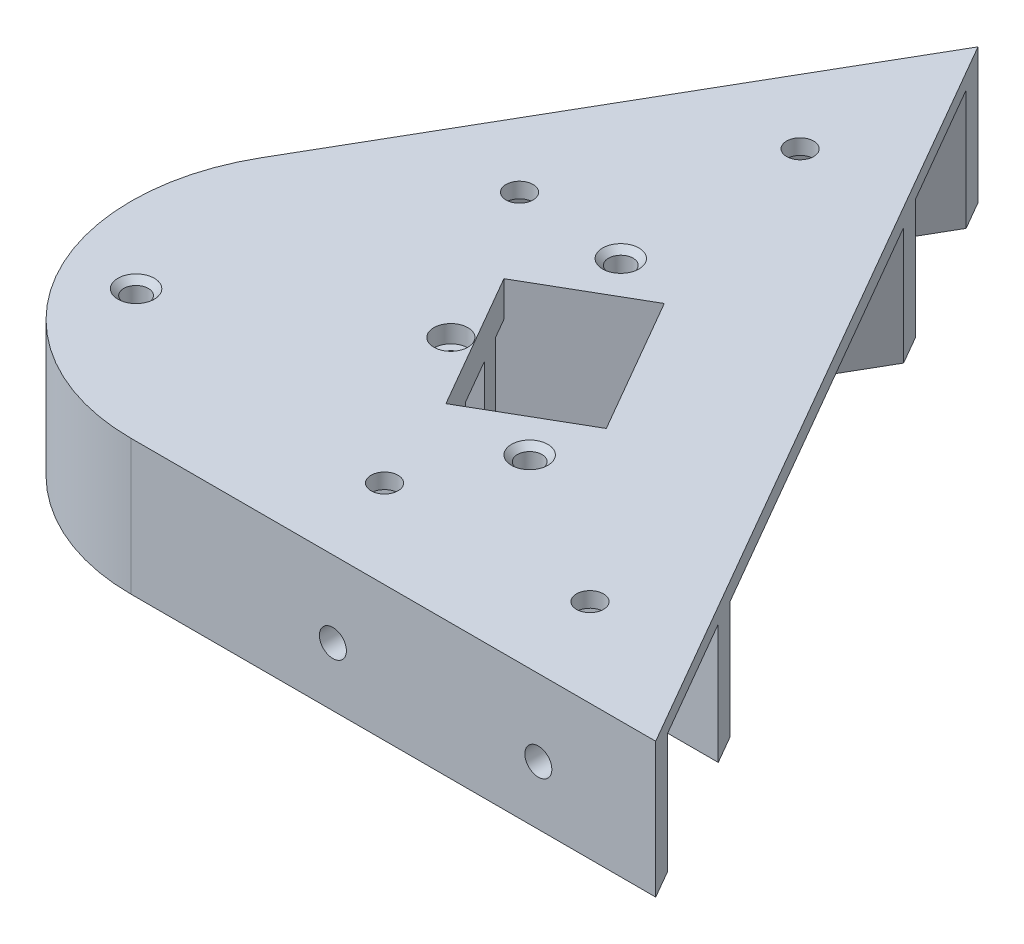
SolidWorks part; units mm, degrees
other "Markup1"
sketch "Sketch26" plane through (25.6218, 0, -129.9038) normal (-0.1134, -0.9932, -0.0259) x (0.9576, -0.1162, 0.2636)
ref_plane "Front Plane" through (0, 0, 0) normal (0, 0, 1) x (1, 0, 0)
ref_plane "Top Plane" through (0, 0, 0) normal (0, 1, 0) x (1, 0, 0)
ref_plane "Right Plane" through (0, 0, 0) normal (1, 0, 0) x (0, 0, -1)
sketch "Sketch1" plane through (0, 0, 0) normal (0, 1, 0) x (1, 0, 0)
  line L0 (0, 0) -> (150, 0)
  line L1 (0, 0) -> (75, 129.9038)
  line L2 (75, 129.9038) -> (150, 0)
  dimension "D1" = 60
  dimension "D2" = 150
  dimension "D3" = 60
extrude "Boss-Extrude1" add sketch "Sketch1" along normal blind 23
sketch "Sketch2" plane through (0, 0, 0) normal (0, 1, 0) x (1, 0, 0)
  line L0 (0, 0) -> (150, 0) construction
  line L1 (74, 5) -> (174, 5) construction
  line L2 (74, 5) -> (74, 25) construction
  line L3 (74, 25) -> (174, 25) construction
  line L4 (174, 5) -> (174, 25) construction
  line L5 (41.3301, 61.5859) -> (91.3301, 148.1884) construction
  line L6 (91.3301, 148.1884) -> (108.6506, 138.1884) construction
  line L7 (108.6506, 138.1884) -> (58.6506, 51.5859) construction
  line L8 (58.6506, 51.5859) -> (41.3301, 61.5859) construction
  line L9 (75, 129.9038) -> (0, 0) construction
  line L10 (108.9238, 138.2616) -> (58.7238, 51.3127)
  line L11 (58.7238, 51.3127) -> (41.0569, 61.5127)
  line L12 (41.0569, 61.5127) -> (91.2569, 148.4616)
  line L13 (91.2569, 148.4616) -> (108.9238, 138.2616)
  line L14 (73.8, 25.2) -> (174.2, 25.2)
  line L15 (174.2, 4.8) -> (174.2, 25.2)
  line L16 (73.8, 4.8) -> (174.2, 4.8)
  line L17 (73.8, 4.8) -> (73.8, 25.2)
  dimension "D1" = 20
  dimension "D2" = 5
  dimension "D3" = 74
  dimension "D4" = 20
  dimension "D5" = 74
  dimension "D6" = 5
  dimension "D7" = 100
  dimension "D8" = 100
  dimension "D9" = 0.2
  dimension "D10" = 0.2
extrude "Cut-Extrude2" cut sketch "Sketch2" along normal blind 20.4
sketch "Sketch4" plane through (0, 0, 0) normal (0, 1, 0) x (1, 0, 0)
  line L4 (135.4508, 25.2) -> (89.5492, 104.7038) construction
  line L6 (0, 0) -> (52.9457, 91.7047) construction
  line L7 (68.4424, 27.9682) -> (51.1219, 17.9682) construction
  line L8 (68.4424, 27.9682) -> (58.4424, 45.2887) construction
  line L9 (58.4424, 45.2887) -> (41.1219, 35.2887) construction
  line L10 (51.1219, 17.9682) -> (41.1219, 35.2887) construction
  line L11 (68.4424, 27.9682) -> (41.1219, 35.2887) construction
  line L12 (58.4424, 45.2887) -> (51.1219, 17.9682) construction
  line L13 (58.5156, 45.5619) -> (40.8487, 35.3619)
  line L14 (75, 129.9038) -> (0, 0) construction
  line L15 (0, 0) -> (130.8784, 0) construction
  line L16 (0, 0) -> (150, 0) construction
  line L17 (51.0487, 17.695) -> (40.8487, 35.3619)
  line L18 (68.7156, 27.895) -> (51.0487, 17.695)
  line L19 (68.7156, 27.895) -> (58.5156, 45.5619)
  point P0 (54.7821, 31.6285)
  dimension "D1" = 20
  dimension "D2" = 20
  dimension "D4" = 0.2
extrude "Cut-Extrude3" cut sketch "Sketch4" along normal blind 20
sketch "Sketch7" plane through (0, 0, 0) normal (-0.866, 0, -0.5) x (-0.5, 0, 0.866)
  line L0 (-150, 0) -> (0, 0) construction
  line L1 (-150, 23) -> (-150, 0) construction
  circle A0 centre (-130, 10) radius 2.3
  circle A1 centre (-95, 10) radius 2.3
  dimension "D1" = 4.6
  dimension "D2" = 10
  dimension "D3" = 20
  dimension "D4" = 35
extrude "Cut-Extrude6" cut sketch "Sketch7" against normal blind 10
sketch "Sketch8" plane through (0, 0, 0) normal (0, 0, 1) x (1, 0, 0)
  line L0 (150, 23) -> (150, 0) construction
  line L1 (0, 0) -> (150, 0) construction
  circle A0 centre (130, 10) radius 2.3
  circle A1 centre (95, 10) radius 2.3
  dimension "D1" = 4.6
  dimension "D2" = 20
  dimension "D3" = 10
  dimension "D4" = 35
extrude "Cut-Extrude7" cut sketch "Sketch8" against normal blind 10
ref_plane "Plane1" through (42.4846, 0, -24.5285) normal (0.866, 0, -0.5) x (-0.5, 0, -0.866)
fillet "Fillet3" radius 35 1 edges at (0, 11.5, 0)
sketch "Sketch22" plane through (0, 0, 0) normal (0, -1, 0) x (1, 0, 0)
  line L0 (76.2572, -28.4387) -> (62.7572, -51.8213)
  line L1 (62.7572, -51.8213) -> (86.1399, -65.3213)
  line L2 (86.1399, -65.3213) -> (99.6399, -41.9387)
  line L3 (99.6399, -41.9387) -> (76.2572, -28.4387)
  line L5 (135.4508, -25.2) -> (89.5492, -104.7038) construction
  dimension "D1" = 80.26
  dimension "D2" = 13.5
  dimension "D3" = 13.5
  dimension "D4" = 27
extrude "Cut-Extrude11" cut sketch "Sketch22" against normal through all both and the other way through all
sketch "Sketch21" plane through (0, 0, 0) normal (0, -1, 0) x (1, 0, 0)
  line L0 (132.6795, -30) -> (109.9968, -30)
  line L1 (109.9968, -30) -> (80.9791, -80.26)
  line L2 (80.9791, -80.26) -> (92.3205, -99.9038)
  line L3 (92.3205, -99.9038) -> (132.6795, -30)
  line L4 (135.4508, -25.2) -> (89.5492, -104.7038) construction
  line L5 (135.4508, -25.2) -> (73.8, -25.2) construction
  line L7 (58.7238, -51.3127) -> (89.5492, -104.7038) construction
  line L8 (58.7238, -51.3127) -> (89.5492, -104.7038) construction
  line L9 (86.1399, -65.3213) -> (99.6399, -41.9387) construction
  dimension "D1" = 3
  dimension "D2" = 4.8
  dimension "D3" = 4.8
extrude "Cut-Extrude10" cut sketch "Sketch21" against normal offset from surface (20 mm away) 3 up to face at (81.1985, 23, -46.88)
sketch "Sketch27" plane through (0, 23, 0) normal (0, 1, 0) x (1, 0, 0)
  line L0 (76.2572, 28.4387) -> (62.7572, 51.8213)
  line L1 (62.7572, 51.8213) -> (68.8194, 55.3213)
  line L2 (62.7572, 51.8213) -> (86.1399, 65.3213) construction
  line L3 (68.8194, 55.3213) -> (82.3194, 31.9387)
  line L4 (99.6399, 41.9387) -> (76.2572, 28.4387) construction
  line L5 (82.3194, 31.9387) -> (76.2572, 28.4387)
  dimension "D1" = 7
extrude "Boss-Extrude3" add sketch "Sketch27" against normal blind 6
sketch "Sketch28" plane through (0, 17, 0) normal (0, -1, 0) x (1, 0, 0)
  line L0 (74.2572, -31.9028) -> (64.7572, -48.3572)
  line L3 (64.7572, -48.3572) -> (70.8194, -51.8572)
  line L4 (70.8194, -51.8572) -> (80.3194, -35.4028)
  line L5 (80.3194, -35.4028) -> (74.2572, -31.9028)
  line L6 (76.2572, -28.4387) -> (82.3194, -31.9387) construction
  line L7 (62.7572, -51.8213) -> (86.1399, -65.3213) construction
  line L8 (82.3194, -31.9387) -> (68.8194, -55.3213) construction
  line L9 (76.2572, -28.4387) -> (62.7572, -51.8213) construction
  dimension "D2" = 4
  dimension "D3" = 4
extrude "Boss-Extrude4" add sketch "Sketch28" along normal up to surface (17 mm away) up to face at (88.3834, 0, -51.0282)
sketch "Sketch29" plane through (0, 0, 0) normal (0, -1, 0) x (1, 0, 0)
  line L0 (77.8194, -39.7329) -> (71.7572, -36.2329)
  line L1 (70.8194, -51.8572) -> (80.3194, -35.4028) construction
  line L2 (71.7572, -36.2329) -> (67.2572, -44.0271)
  line L3 (67.2572, -44.0271) -> (73.3194, -47.5271)
  line L4 (73.3194, -47.5271) -> (77.8194, -39.7329)
  line L5 (80.3194, -35.4028) -> (74.2572, -31.9028) construction
  line L6 (64.7572, -48.3572) -> (70.8194, -51.8572) construction
  line L7 (76.2572, -28.4387) -> (74.2572, -31.9028) construction
  dimension "D1" = 5
  dimension "D2" = 5
extrude "Cut-Extrude14" cut sketch "Sketch29" against normal up to surface (17 mm away) up to face at (78.2883, 17, -31.9207)
sketch "Sketch30" plane through (0, 17, 0) normal (0, -1, 0) x (1, 0, 0)
  line L0 (75.5694, -43.63) -> (63.6156, -36.7285) construction
  line L1 (77.8194, -39.7329) -> (73.3194, -47.5271) construction
  line L2 (68.7156, -27.895) -> (58.5156, -45.5619) construction
  circle A0 centre (72.9713, -42.13) radius 1.5
  dimension "D1" = 3
  dimension "D2" = 3
extrude "Cut-Extrude15" cut sketch "Sketch30" against normal through all
sketch "Sketch31" plane through (0, 23, 0) normal (0, 1, 0) x (1, 0, 0)
  circle A0 centre (72.9713, 42.13) radius 2.9
  dimension "D1" = 5.8
extrude "Cut-Extrude17" cut sketch "Sketch31" against normal blind 3
sketch "Sketch32" plane through (0, 0, -30) normal (0, 0, -1) x (-1, 0, 0)
  line L0 (-132.6795, 10) -> (-109.9968, 10) construction
  line L1 (-132.6795, 20) -> (-132.6795, 0) construction
  line L2 (-109.9968, 20) -> (-109.9968, 0) construction
  circle A0 centre (-121.3381, 10) radius 2.3
  dimension "D1" = 4.6
extrude "Cut-Extrude18" cut sketch "Sketch32" against normal blind 10
sketch "Sketch33" plane through (25.9808, 0, 15) normal (0.866, 0, 0.5) x (0.5, 0, -0.866)
  line L0 (109.9968, 10) -> (132.6795, 10) construction
  line L1 (109.9968, 20) -> (109.9968, 0) construction
  line L2 (132.6795, 20) -> (132.6795, 0) construction
  circle A0 centre (121.3381, 10) radius 2.3
  dimension "D1" = 4.6
extrude "Cut-Extrude19" cut sketch "Sketch33" against normal blind 10
sketch "Sketch34" plane through (45.9487, 0, -26.5285) normal (0.866, 0, -0.5) x (-0.5, 0, -0.866)
  line L0 (-10.2, 10) -> (10.2, 10) construction
  line L1 (-10.2, 20) -> (-10.2, 0) construction
  line L2 (10.2, 20) -> (10.2, 0) construction
  circle A0 centre (0, 10) radius 2.3
  dimension "D1" = 4.6
extrude "Cut-Extrude20" cut sketch "Sketch34" against normal through all
ref_plane "Plane2" through (41.6185, 0, -24.0285) normal (0.866, 0, -0.5) x (-0.5, 0, -0.866)
sketch "Sketch35" plane through (41.6185, 0, -24.0285) normal (0.866, 0, -0.5) x (-0.5, 0, -0.866)
  circle A0 centre (0, 10) radius 4
  dimension "D1" = 8
extrude "Cut-Extrude21" cut sketch "Sketch35" against normal through all
sketch "Sketch36" plane through (0, 23, 0) normal (0, 1, 0) x (1, 0, 0)
  line L0 (0, 0) -> (112.5, 64.9519) construction
  line L1 (150, 0) -> (75, 129.9038) construction
  circle A0 centre (38.9711, 22.5) radius 2.1
  dimension "D1" = 4.2
  dimension "D2" = 45
extrude "Cut-Extrude22" cut sketch "Sketch36" against normal blind 5
sketch "Sketch37" plane through (0, 23, 0) normal (0, 1, 0) x (1, 0, 0)
  line L0 (0, 0) -> (98.694, 88.8645) construction
  line L1 (150, 0) -> (75, 129.9038) construction
  line L3 (0, 0) -> (112.5, 64.9519) construction
  line L4 (0, 0) -> (126.306, 41.0393) construction
  circle A0 centre (97.0078, 31.5197) radius 2.1
  circle A1 centre (75.8008, 68.2513) radius 2.1
  dimension "D5" = 4.2
  dimension "D6" = 4.2
  dimension "D1" = 12
  dimension "D2" = 12
  dimension "D3" = 102
  dimension "D4" = 102
extrude "Cut-Extrude23" cut sketch "Sketch37" against normal blind 5
sketch "Sketch38" plane through (0, 20.4, 0) normal (0, -1, 0) x (1, 0, 0)
  line L0 (49.8904, -56.4127) -> (83.6603, -114.9038) construction
  line L1 (41.0569, -61.5127) -> (58.7238, -51.3127) construction
  line L2 (77.7713, -125.1038) -> (89.5492, -104.7038) construction
  line L3 (73.8, -15) -> (141.3397, -15) construction
  line L4 (73.8, -25.2) -> (73.8, -4.8) construction
  line L5 (135.4508, -25.2) -> (147.2287, -4.8) construction
  line L6 (41.0569, -61.5127) -> (58.7238, -51.3127) construction
  circle A0 centre (88.8, -15) radius 2.3
  circle A1 centre (123.8, -15) radius 2.3
  circle A2 centre (57.3904, -69.4031) radius 2.3
  circle A3 centre (74.8904, -99.7139) radius 2.3
  dimension "D1" = 4.6
  dimension "D2" = 15
  dimension "D3" = 35
  dimension "D4" = 15
  dimension "D5" = 35
extrude "Cut-Extrude24" cut sketch "Sketch38" against normal blind 10
chamfer "Chamfer1" distance 1 angle 45 3 edges at (38.9711, 23, -20.4) (75.8008, 23, -66.1513) (97.0078, 23, -29.4197)
